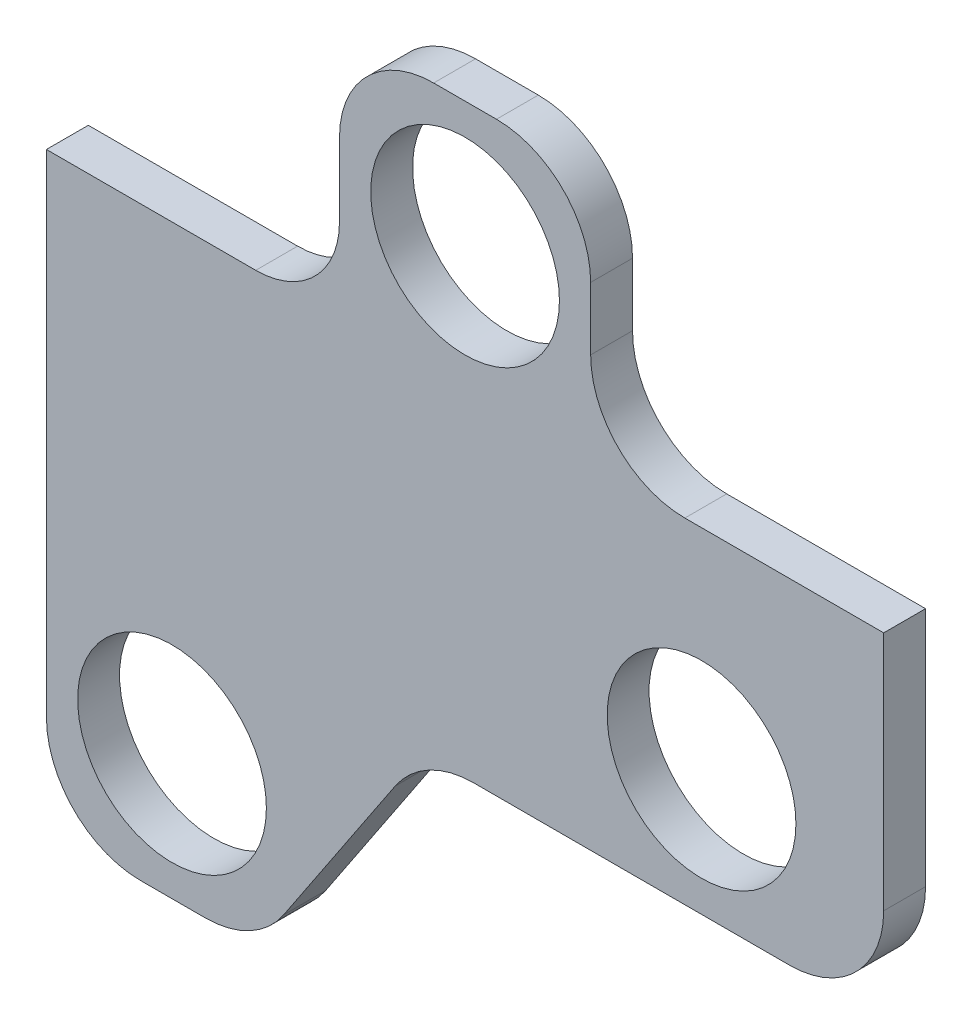
SolidWorks part; units mm, degrees
ref_plane "Front Plane" through (0, 0, 0) normal (0, 0, 1) x (1, 0, 0)
ref_plane "Top Plane" through (0, 0, 0) normal (0, 1, 0) x (1, 0, 0)
ref_plane "Right Plane" through (0, 0, 0) normal (1, 0, 0) x (0, 0, -1)
sketch "Sketch1" plane through (0, 0, 0) normal (0, 0, 1) x (1, 0, 0)
  line L0 (63.5, -6.35) -> (-6.35, -6.35)
  line L1 (-63.5, 44.45) -> (63.5, 44.45)
  line L2 (-63.5, 44.45) -> (-63.5, -44.45)
  line L3 (-63.5, -44.45) -> (63.5, -44.45)
  line L4 (63.5, 44.45) -> (63.5, -44.45)
  line L5 (-63.5, 44.45) -> (63.5, -44.45) construction
  line L6 (-63.5, -44.45) -> (63.5, 44.45) construction
  line L7 (-6.35, -6.35) -> (-31.75, -44.45)
  circle A0 centre (-44.45, -25.4) radius 14.3129
  circle A1 centre (35.8719, 12.7) radius 14.3129
  point P0 (0, 0)
  dimension "D1" = 28.6258
  dimension "D2" = 28.6258
  dimension "D3" = 88.9
  dimension "D4" = 19.05
  dimension "D5" = 57.15
  dimension "D6" = 88.9
  dimension "D7" = 19.05
  dimension "D8" = 127
  dimension "D9" = 38.1
  dimension "D10" = 31.75
  dimension "D11" = 57.15
extrude "Boss-Extrude1" add sketch "Sketch1" along normal blind 6.35 contours L7 L0 L4 L1 L2 L3 A1 A0
fillet "Fillet1" radius 14.2875 4 edges at (63.5, -6.35, 3.175) (-6.35, -6.35, 3.175) (-31.75, -44.45, 3.175) (-63.5, -44.45, 3.175)
sketch "Sketch2" plane through (0, 0, 6.35) normal (0, 0, 1) x (1, 0, 0)
  line L0 (-63.5, 44.45) -> (63.5, 44.45) construction
  line L1 (-19.05, 44.45) -> (19.05, 44.45)
  line L2 (-19.05, 44.45) -> (-19.05, 82.55)
  line L3 (-19.05, 82.55) -> (19.05, 82.55)
  line L4 (19.05, 44.45) -> (19.05, 82.55)
  line L5 (-63.5, 44.45) -> (-63.5, -30.1625) construction
  dimension "D1" = 38.1
  dimension "D2" = 44.45
  dimension "D3" = 38.1
extrude "Boss-Extrude2" add sketch "Sketch2" against normal blind 6.35
fillet "Fillet2" radius 14.2875 3 edges at (-19.05, 82.55, 3.175) (19.05, 82.55, 3.175) (19.05, 44.45, 3.175)
sketch "Sketch3" plane through (0, 0, 6.35) normal (0, 0, 1) x (1, 0, 0)
  line L1 (4.7625, 82.55) -> (-4.7625, 82.55) construction
  circle A0 centre (0, 63.5) radius 14.3129
  circle A1 centre (35.8719, 12.7) radius 14.3129 construction
  dimension "D1" = 28.6258
  dimension "D2" = 35.8719
  dimension "D3" = 19.05
extrude "Cut-Extrude1" cut sketch "Sketch3" against normal through all
sketch "Sketch4" plane through (0, 0, 6.35) normal (0, 0, 1) x (1, 0, 0)
  circle A0 centre (-25.4, 63.5) radius 2.3813
  circle A1 centre (25.4, 63.5) radius 2.3813
  circle A2 centre (0, 63.5) radius 14.2875
  circle A3 centre (0, 63.5) radius 25.4 construction
  dimension "D1" = 50.8
  dimension "D2" = 4.7625
  dimension "D3" = 4.7625
extrude "Cut-Extrude2" [suppressed] cut sketch "Sketch4" against normal through all
fillet "Fillet3" radius 12.7 1 edges at (-19.05, 44.45, 3.175)
